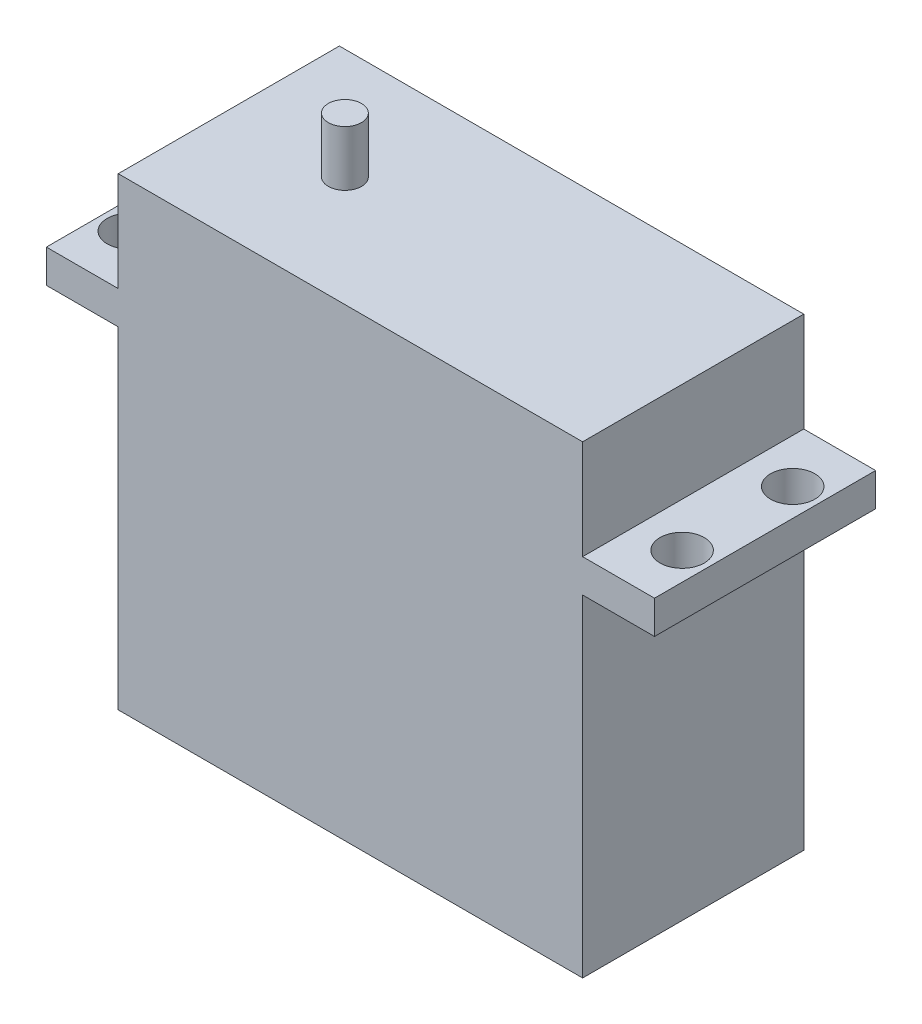
SolidWorks part; units mm, degrees
ref_plane "前视基准面" through (0, 0, 0) normal (0, 0, 1) x (1, 0, 0)
ref_plane "上视基准面" through (0, 0, 0) normal (0, 1, 0) x (1, 0, 0)
ref_plane "右视基准面" through (0, 0, 0) normal (1, 0, 0) x (0, 0, -1)
ref_plane "基准面1" through (0, 0, 20) normal (0, 0, 1) x (1, 0, 0)
sketch "草图1" plane through (0, 0, 20) normal (0, 0, 1) x (1, 0, 0)
  line L0 (48.5, 42) -> (-6.5, 42)
  line L1 (-6.5, 42) -> (-6.5, 0)
  line L2 (-6.5, 0) -> (48.5, 0)
  line L3 (48.5, 0) -> (48.5, 42)
extrude "凸台-拉伸1" add sketch "草图1" against normal blind 20
sketch "草图2" plane through (0, 0, 0) normal (0, 0, -1) x (-1, 0, 0)
  line L0 (6.5, 42) -> (0, 42)
  line L1 (0, 42) -> (0, 33)
  line L2 (0, 33) -> (6.5, 33)
  line L3 (6.5, 33) -> (6.5, 42)
extrude "切除-拉伸1" cut sketch "草图2" against normal through all
sketch "草图3" plane through (0, 0, 0) normal (0, 0, -1) x (-1, 0, 0)
  line L0 (6.5, 0) -> (6.5, 30)
  line L1 (6.5, 30) -> (0, 30)
  line L2 (0, 30) -> (0, 0)
  line L3 (0, 0) -> (6.5, 0)
extrude "切除-拉伸2" cut sketch "草图3" against normal through all
sketch "草图4" plane through (0, 0, 0) normal (0, 0, -1) x (-1, 0, 0)
  line L0 (-48.5, 0) -> (-42, 0)
  line L1 (-42, 0) -> (-42, 30)
  line L2 (-42, 30) -> (-48.5, 30)
  line L3 (-48.5, 30) -> (-48.5, 0)
extrude "切除-拉伸3" cut sketch "草图4" against normal through all
sketch "草图5" plane through (0, 0, 0) normal (0, 0, -1) x (-1, 0, 0)
  line L0 (-48.5, 42) -> (-48.5, 33)
  line L1 (-48.5, 33) -> (-42, 33)
  line L2 (-42, 33) -> (-42, 42)
  line L3 (-42, 42) -> (-48.5, 42)
extrude "切除-拉伸4" cut sketch "草图5" against normal through all
ref_plane "基准面2" through (0, 0, 10) normal (0, 0, -1) x (-1, 0, 0)
sketch "草图6" plane through (0, 0, 10) normal (0, 0, -1) x (-1, 0, 0)
  line L0 (-13.5, 42) -> (-10.5, 42)
  line L1 (-10.5, 42) -> (-10.5, 47)
  line L2 (-10.5, 47) -> (-13.5, 47)
  line L3 (-13.5, 47) -> (-13.5, 42)
  line L4 (-10.5, 42) -> (-10.5, 47) construction
revolve "旋转1" add sketch "草图6" angle 360 about L4
hole_wizard "Ø2.0 (2) 直径孔1" positions "草图8" profile "草图7" hole size "Ø2.0" standard "ANSI Metric"
sketch "草图8" plane through (0, 33, 0) normal (0, 1, 0) x (1, 0, 0)
  point P0 (46, -15)
  point P1 (-4, -5)
  point P2 (-4, -15)
  point P3 (46, -5)
sketch "草图7" plane through (46, 33, 15) normal (1, 0, 0) x (0, 0, 1)
  line L0 (0, 0) -> (0, 33)
  line L1 (0, 33) -> (1, 33)
  line L2 (1, 33) -> (1, 0)
  line L5 (1, 0) -> (0, 0)
  line L11 (0, -6.35) -> (0, 107.95) construction
  dimension "通孔孔直径" = 2
  dimension "通孔孔深度" = 33
sketch "草图9" plane through (0, 47, 0) normal (0, 1, 0) x (1, 0, 0)
  circle A0 centre (10.5, -10) radius 1.5
  circle A1 centre (10.5, -10) radius 3
extrude "切除-拉伸5" cut sketch "草图9" against normal blind 5
sketch "草图10" plane through (0, 33, 0) normal (0, 1, 0) x (1, 0, 0)
  circle A0 centre (46, -15) radius 2
  circle A1 centre (46, -5) radius 2
  circle A2 centre (-4, -5) radius 2
  circle A3 centre (-4, -15) radius 2
  dimension "D1" = 2
  dimension "D2" = 2
extrude "切除-拉伸6" cut sketch "草图10" against normal blind 5
